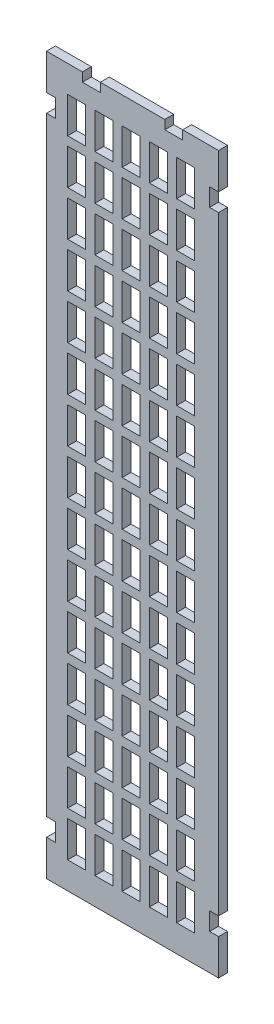
SolidWorks part; units mm, degrees
ref_plane "Front Plane" through (0, 0, 0) normal (0, 0, 1) x (1, 0, 0)
ref_plane "Top Plane" through (0, 0, 0) normal (0, 1, 0) x (1, 0, 0)
ref_plane "Right Plane" through (0, 0, 0) normal (1, 0, 0) x (0, 0, -1)
sketch "Sketch1" plane through (0, 0, 0) normal (0, 0, 1) x (1, 0, 0)
  line L0 (12.7, -254) -> (48.26, -254)
  line L1 (0, 0) -> (60.96, 0)
  line L2 (0, 0) -> (0, -254)
  line L3 (0, -254) -> (12.7, -254)
  line L4 (60.96, 0) -> (60.96, -254)
  line L5 (12.7, 0) -> (19.05, 0)
  line L6 (12.7, 0) -> (12.7, -3.175)
  line L7 (12.7, -3.175) -> (19.05, -3.175)
  line L8 (19.05, 0) -> (19.05, -3.175)
  line L9 (41.91, 0) -> (48.26, 0)
  line L10 (41.91, 0) -> (41.91, -3.175)
  line L11 (41.91, -3.175) -> (48.26, -3.175)
  line L12 (48.26, 0) -> (48.26, -3.175)
  line L13 (60.96, -12.7) -> (57.785, -12.7)
  line L14 (60.96, -12.7) -> (60.96, -19.05)
  line L15 (60.96, -19.05) -> (57.785, -19.05)
  line L16 (57.785, -12.7) -> (57.785, -19.05)
  line L17 (60.96, -234.95) -> (57.785, -234.95)
  line L18 (60.96, -234.95) -> (60.96, -241.3)
  line L19 (60.96, -241.3) -> (57.785, -241.3)
  line L20 (57.785, -234.95) -> (57.785, -241.3)
  line L25 (48.26, -254) -> (60.96, -254)
  line L29 (0, -241.3) -> (3.175, -241.3)
  line L30 (0, -241.3) -> (0, -234.95)
  line L31 (0, -234.95) -> (3.175, -234.95)
  line L32 (3.175, -241.3) -> (3.175, -234.95)
  line L33 (0, -19.05) -> (3.175, -19.05)
  line L34 (0, -19.05) -> (0, -12.7)
  line L35 (0, -12.7) -> (3.175, -12.7)
  line L36 (3.175, -19.05) -> (3.175, -12.7)
  dimension "D1" = 60.96
  dimension "D2" = 254
  dimension "D3" = 12.7
  dimension "D4" = 6.35
  dimension "D5" = 3.175
  dimension "D6" = 6.35
  dimension "D7" = 3.175
  dimension "D8" = 12.7
  dimension "D9" = 12.7
  dimension "D10" = 6.35
  dimension "D11" = 3.175
  dimension "D12" = 3.175
  dimension "D13" = 6.35
  dimension "D14" = 12.7
  dimension "D21" = 3.175
  dimension "D22" = 6.35
  dimension "D23" = 12.7
  dimension "D24" = 12.7
  dimension "D25" = 6.35
  dimension "D26" = 3.175
extrude "Boss-Extrude1" add sketch "Sketch1" along normal blind 3.175
sketch "Sketch2" plane through (0, 0, 3.175) normal (0, 0, 1) x (1, 0, 0)
  line L0 (12.7, -3.175) -> (19.05, -3.175) construction
  line L1 (7.493, -9.525) -> (13.8445, -9.525)
  line L2 (7.493, -9.525) -> (7.493, -22.225)
  line L3 (7.493, -22.225) -> (13.8445, -22.225)
  line L4 (13.8445, -9.525) -> (13.8445, -22.225)
  line L5 (7.493, -9.525) -> (13.8445, -22.225) construction
  line L6 (7.493, -22.225) -> (13.8445, -9.525) construction
  line L7 (3.175, -19.05) -> (3.175, -12.7) construction
  point P0 (10.6688, -15.875)
  dimension "D1" = 6.35
  dimension "D2" = 4.318
  dimension "D3" = 6.3515
  dimension "D4" = 12.7
extrude "Cut-Extrude1" cut sketch "Sketch2" against normal blind 5.08
pattern_linear "LPattern1" count 5 spacing 9.652 along (1, 0, 0) count 15 spacing 15.875 along (0, -1, 0) of "Cut-Extrude1"
